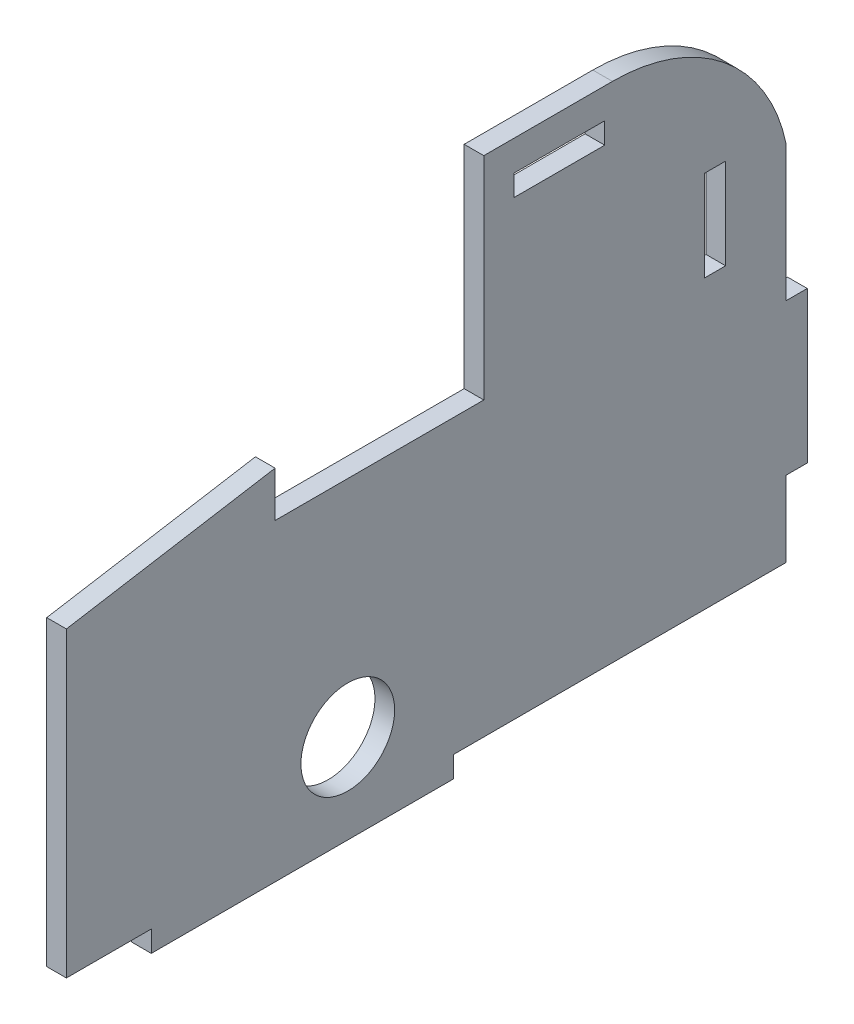
SolidWorks part; units mm, degrees
ref_plane "Front Plane" through (0, 0, 0) normal (0, 0, 1) x (1, 0, 0)
ref_plane "Top Plane" through (0, 0, 0) normal (0, 1, 0) x (1, 0, 0)
ref_plane "Right Plane" through (0, 0, 0) normal (1, 0, 0) x (0, 0, -1)
sketch "Sketch1" plane through (0, 0, 0) normal (1, 0, 0) x (0, 0, -1)
  line L0 (-31.2286, 0) -> (-31.2286, 20)
  line L5 (55, 0) -> (-55, 0) construction
  line L6 (-31.2286, 20) -> (-17.4206, 22.3107)
  line L7 (-17.4206, 22.3107) -> (-17.4206, 19.3107)
  line L8 (-17.4206, 19.3107) -> (-3.6126, 19.3107)
  line L9 (-3.6126, 19.3107) -> (-3.6126, 33.3107)
  line L10 (-3.6126, 33.3107) -> (4.8986, 33.3107)
  line L11 (16.3874, 24) -> (16.3874, 0)
  line L13 (16.3874, 0) -> (0, 0)
  line L14 (0, 0) -> (-31.2286, 0)
  line L15 (-3.6126, 33.3107) -> (4.8986, 33.3107) construction
  line L16 (4.8986, 33.3107) -> (16.3874, 33.3107) construction
  line L17 (-31.2286, 20) -> (-17.4206, 19.3107) construction
  line L18 (16.3874, 33.3107) -> (16.3874, 24) construction
  line L19 (4.8986, 33.3107) -> (16.3874, 33.3107) construction
  line L20 (-17.4206, 22.3107) -> (-3.6126, 24.6213) construction
  line L21 (-31.2286, 20) -> (18.8539, 20) construction
  arc A0 (4.8986, 33.3107) -> (16.3874, 24) centre (4.8986, 21.5671) cw
  dimension "D1" = 9.5
  dimension "D2" = 14
  dimension "D3" = 3
  dimension "D4" = 20
  dimension "D5" = 20
  dimension "D6" = 24
  dimension "D7" = 14
  dimension "D8" = 14
extrude "Boss-Extrude1" add sketch "Sketch1" along normal blind 1.3
sketch "Sketch2" plane through (1.3, 0, 0) normal (1, 0, 0) x (0, 0, -1)
  line L0 (55, 0) -> (-55, 0) construction
  line L1 (-25.6126, 0) -> (-5.6126, 0)
  line L2 (-25.6126, 0) -> (-25.6126, -1.4)
  line L3 (-25.6126, -1.4) -> (-5.6126, -1.4)
  line L4 (-5.6126, 0) -> (-5.6126, -1.4)
  line L5 (16.3874, 0) -> (16.3874, 24) construction
  line L6 (16.3874, 15) -> (17.7874, 15)
  line L7 (16.3874, 15) -> (16.3874, 5)
  line L8 (16.3874, 5) -> (17.7874, 5)
  line L9 (17.7874, 15) -> (17.7874, 5)
  dimension "D1" = 1.4
  dimension "D2" = 1.4
  dimension "D3" = 10
  dimension "D4" = 20
  dimension "D5" = 22
  dimension "D6" = 5
extrude "Boss-Extrude2" add sketch "Sketch2" against normal blind 1.3
sketch "Sketch3" plane through (1.3, 0, 0) normal (1, 0, 0) x (0, 0, -1)
  line L0 (-3.6126, 33.3107) -> (-3.6126, 19.3107) construction
  line L1 (-1.6126, 31.3107) -> (4.3874, 31.3107)
  line L2 (-1.6126, 31.3107) -> (-1.6126, 29.9107)
  line L3 (-1.6126, 29.9107) -> (4.3874, 29.9107)
  line L4 (4.3874, 31.3107) -> (4.3874, 29.9107)
  line L5 (10.9874, 25) -> (12.3874, 25)
  line L6 (10.9874, 25) -> (10.9874, 19)
  line L7 (10.9874, 19) -> (12.3874, 19)
  line L8 (12.3874, 25) -> (12.3874, 19)
  line L9 (4.8986, 33.3107) -> (-3.6126, 33.3107) construction
  line L10 (16.3874, 15) -> (16.3874, 24) construction
  line L11 (17.7874, 15) -> (16.3874, 15) construction
  dimension "D1" = 6
  dimension "D2" = 1.4
  dimension "D3" = 1.4
  dimension "D4" = 6
  dimension "D5" = 2
  dimension "D6" = 2
  dimension "D7" = 4
  dimension "D8" = 4
extrude "Cut-Extrude1" cut sketch "Sketch3" against normal through all
sketch "Sketch4" plane through (1.3, 0, 0) normal (1, 0, 0) x (0, 0, -1)
  line L0 (16.3874, 0) -> (16.3874, 5) construction
  line L2 (55, 0) -> (-55, 0) construction
  circle A0 centre (-12.6126, 4.5) radius 3.1
  dimension "D2" = 6.2
  dimension "D3" = 4.5
  dimension "D1" = 29
extrude "Cut-Extrude2" cut sketch "Sketch4" against normal through all
